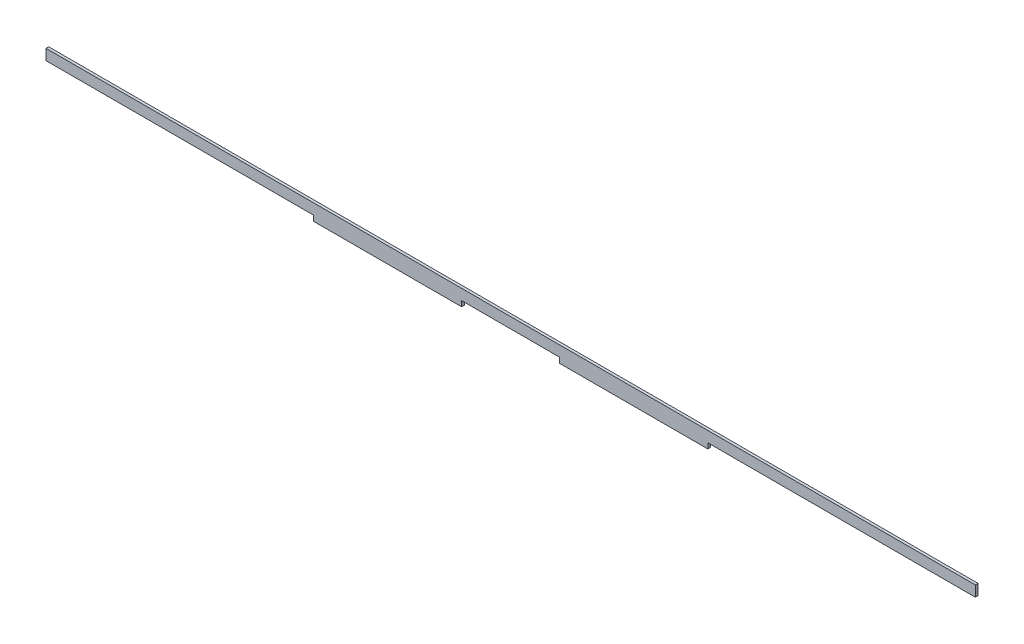
SolidWorks part; units mm, degrees
ref_plane "Front Plane" through (0, 0, 0) normal (0, 0, 1) x (1, 0, 0)
ref_plane "Top Plane" through (0, 0, 0) normal (0, 1, 0) x (1, 0, 0)
ref_plane "Right Plane" through (0, 0, 0) normal (1, 0, 0) x (0, 0, -1)
sketch "Sketch1" plane through (0, 0, 0) normal (0, 0, 1) x (1, 0, 0)
  line L0 (-250.1625, 19.7158) -> (791.8375, 19.7158)
  line L1 (325.8375, 7.7158) -> (215.8375, 7.7158)
  line L2 (270.8375, 7.7158) -> (270.8375, 19.7158) construction
  line L3 (791.8375, 19.7158) -> (791.8375, 7.7158)
  line L4 (-250.1625, 19.7158) -> (-250.1625, 7.7158)
  line L5 (-250.1625, 7.7158) -> (49.8375, 7.7158)
  line L6 (49.8375, 7.7158) -> (49.8375, 1.7158)
  line L7 (49.8375, 1.7158) -> (215.8375, 1.7158)
  line L8 (215.8375, 1.7158) -> (215.8375, 7.7158)
  line L9 (791.8375, 7.7158) -> (491.8375, 7.7158)
  line L10 (325.8375, 1.7158) -> (325.8375, 7.7158)
  line L11 (491.8375, 1.7158) -> (325.8375, 1.7158)
  line L12 (491.8375, 7.7158) -> (491.8375, 1.7158)
  dimension "D1" = 55
  dimension "D2" = 6
  dimension "170." = 166
  dimension "D3" = 300
  dimension "D4" = 12
  dimension "D5" = 6
extrude "Boss-Extrude1" add sketch "Sketch1" along normal blind 3 contours L7 L8 L1 L10 L11 L12 L9 L3 L0 L4 L5 L6
